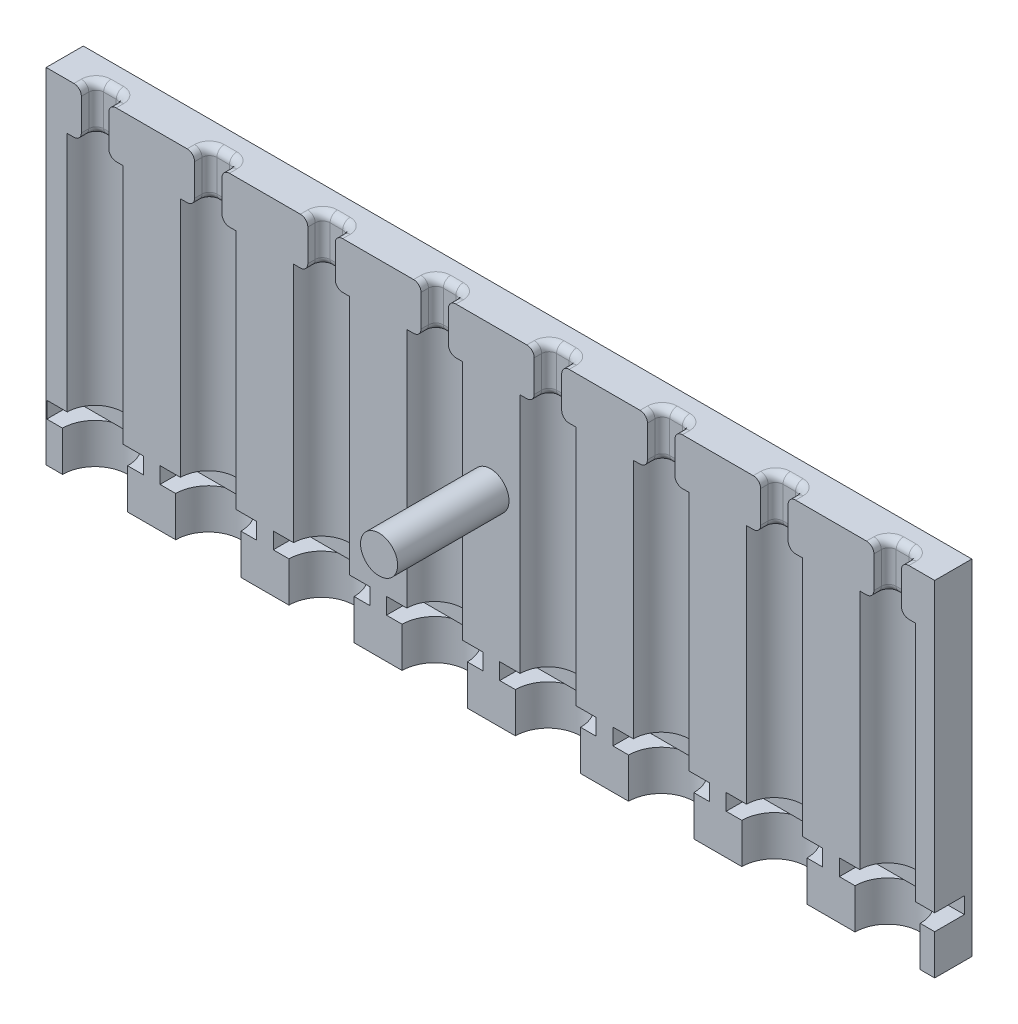
SolidWorks part; units mm, degrees
ref_plane "Front Plane" through (0, 0, 0) normal (1, 0, 0) x (0, 1, 0)
ref_plane "Top Plane" through (0, 0, 0) normal (0, 0, 1) x (0, 1, 0)
ref_plane "Right Plane" through (0, 0, 0) normal (0, 1, 0) x (-1, 0, 0)
sketch "Sketch1" plane through (0, 0, 0) normal (0, 0, 1) x (0, 1, 0)
  line L1 (-75, -150) -> (75, -150)
  line L2 (-75, -150) -> (-75, 150)
  line L3 (-75, 150) -> (75, 150)
  line L4 (75, -150) -> (75, 150)
  line L5 (-75, -150) -> (75, 150) construction
  line L6 (-75, 150) -> (75, -150) construction
  point P0 (0, 0)
  dimension "D1" = 300
  dimension "D2" = 150
extrude "Boss-Extrude1" add sketch "Sketch1" along normal blind 10
sketch "flange slit" plane through (0, 0, 10) normal (0, 0, 1) x (1, 0, 0)
  line L0 (0, 75) -> (0, -75) construction
  line L1 (150, 75) -> (-150, 75) construction
  line L2 (-150, -75) -> (150, -75) construction
  line L3 (-124, 0) -> (150, 0) construction
  line L5 (150, -75) -> (150, 75) construction
  line L6 (-70.7884, -63.1) -> (-70.7884, -60.9) construction
  line L7 (-150, 75) -> (-124, 75) construction
  line L9 (-150, -75) -> (-124, -75) construction
  line L11 (-70.7884, -63.1) -> (-70.7884, -62) construction
  line L12 (-150, -59.8) -> (-124, -59.8)
  line L13 (-150, -59.8) -> (-150, -64.2)
  line L14 (-150, -64.2) -> (-124, -64.2)
  line L19 (-124, -59.8) -> (-124, -64.2)
  line L20 (-150, -59.8) -> (-124, -64.2) construction
  line L21 (-150, -64.2) -> (-124, -59.8) construction
  line L26 (-70.7884, -62) -> (-150, -62) construction
  point P8 (-137, -62)
  dimension "D1" = 26
  dimension "D2" = 2.2
extrude "Flange Slot" cut sketch "flange slit" against normal blind 8
sketch "Sketch3" plane through (0, 0, 10) normal (0, 0, 1) x (1, 0, 0)
  line L0 (-150, -75) -> (150, -75) construction
  line L1 (-150, 75) -> (-124, 75) construction
  line L2 (-150, 75) -> (-150, -75) construction
  line L3 (-150, -75) -> (-124, -75) construction
  line L4 (-124, 75) -> (-124, -75) construction
  line L5 (-150, 75) -> (-124, -75) construction
  line L6 (-150, -75) -> (-124, 75) construction
  line L7 (-124, -64.2) -> (-124, -59.8) construction
  line L8 (-124, -59.8) -> (-150, -59.8) construction
  line L9 (-144.5, -59.8) -> (-129.5, -59.8)
  line L10 (-144.5, -59.8) -> (-144.5, 5.2)
  line L11 (-144.5, 5.2) -> (-129.5, 5.2)
  line L12 (-129.5, -59.8) -> (-129.5, 5.2)
  line L13 (-144.5, -59.8) -> (-129.5, 5.2) construction
  line L14 (-144.5, 5.2) -> (-129.5, -59.8) construction
  line L15 (-137, 75) -> (-137, -59.8) construction
  line L16 (-137, 5.2) -> (-137, -59.8)
  line L18 (-144.5, 5.2) -> (-137, 5.2)
  line L19 (-144.5, 5.2) -> (-144.5, -59.8)
  line L20 (-144.5, -59.8) -> (-137, -59.8)
  line L21 (-137, 5.2) -> (-137, -59.8)
  line L22 (-144.5, 5.2) -> (-137, -59.8) construction
  line L23 (-144.5, -59.8) -> (-137, 5.2) construction
  point P4 (-137, 0)
  point P14 (-137, -27.3)
  point P23 (-140.75, -27.3)
  dimension "D1" = 65
  dimension "D2" = 15
revolve "Syringe Body Slot" cut sketch "Sketch3" angle 360 about L15
sketch "Sketch6" plane through (0, 0, 10) normal (0, 0, 1) x (0, -1, 0)
  line L0 (75, 150) -> (-75, 150) construction
  line L1 (-75, -150) -> (-17.7492, -150)
  line L2 (-75, -150) -> (-75, 150)
  line L3 (-75, 150) -> (-17.7492, 150)
  line L4 (-17.7492, -150) -> (-17.7492, 150)
  line L5 (-75, -150) -> (-17.7492, 150) construction
  line L6 (-75, 150) -> (-17.7492, -150) construction
  point P4 (-46.3746, 0)
extrude "Cut-Extrude2" cut sketch "Sketch6" against normal through all
sketch "Sketch7" plane through (0, 0, 10) normal (0, 0, 1) x (1, 0, 0)
  line L0 (-150, -64.2) -> (-124, -64.2) construction
  line L1 (-137, -64.2) -> (-145.7782, -64.2)
  line L2 (-137, -64.2) -> (-137, -75)
  line L3 (-137, -75) -> (-145.7782, -75)
  line L4 (-145.7782, -64.2) -> (-145.7782, -75)
  line L5 (-137, -64.2) -> (-145.7782, -75) construction
  line L6 (-137, -75) -> (-145.7782, -64.2) construction
  line L7 (-150, -75) -> (150, -75) construction
  point P4 (-141.3891, -69.6)
revolve "Plunger Slot" cut sketch "Sketch7" angle 360 about L2
sketch "Sketch8" plane through (0, 0, 10) normal (0, 0, 1) x (1, 0, 0)
  line L0 (-144.5, 5.2) -> (-129.5, 5.2) construction
  line L1 (-140.7, -7.3492) -> (-133.3, -7.3492)
  line L2 (-140.7, -7.3492) -> (-140.7, 17.7492)
  line L3 (-140.7, 17.7492) -> (-133.3, 17.7492)
  line L4 (-133.3, -7.3492) -> (-133.3, 17.7492)
  line L5 (-140.7, -7.3492) -> (-133.3, 17.7492) construction
  line L6 (-140.7, 17.7492) -> (-133.3, -7.3492) construction
  line L7 (-150, 17.7492) -> (150, 17.7492) construction
  point P0 (-137, 5.2)
  dimension "D1" = 7.4
extrude "Needle Slot" cut sketch "Sketch8" against normal blind 4
fillet "Fillet1" radius 2 8 edges at (-140.7, 17.7492, 8) (-140.7, 5.2, 8) (-133.3, 17.7492, 8) (-133.3, 5.2, 8) (-140.7, 11.4746, 6) (-137, 17.7492, 6) (-133.3, 11.4746, 6) (-137, 5.2, 6)
pattern_linear "LPattern3" count 10 spacing 30.5 along (1, 0, 0) of "Plunger Slot", "Syringe Body Slot", "Flange Slot", "Needle Slot", "Fillet1"
sketch "Sketch9" plane through (0, 0, 10) normal (0, 0, 1) x (1, 0, 0)
  circle A0 centre (0, -21.0254) radius 5
  dimension "D1" = 10
extrude "Boss-Extrude3" add sketch "Sketch9" along normal blind 30
sketch "Sketch10" plane through (0, 0, 10) normal (0, 0, 1) x (1, 0, 0)
  line L5 (-128.2218, -75) -> (-115.2782, -75) construction
  line L6 (-150, 17.7492) -> (-119.6762, 17.7492)
  line L7 (-150, 17.7492) -> (-150, -75)
  line L8 (-150, -75) -> (-119.6762, -75)
  line L9 (-119.6762, 17.7492) -> (-119.6762, -75)
extrude "Cut-Extrude3" cut sketch "Sketch10" against normal through all
mirror "Mirror1" about plane through (0, 0, 0) normal (1, 0, 0) of "Cut-Extrude3"
